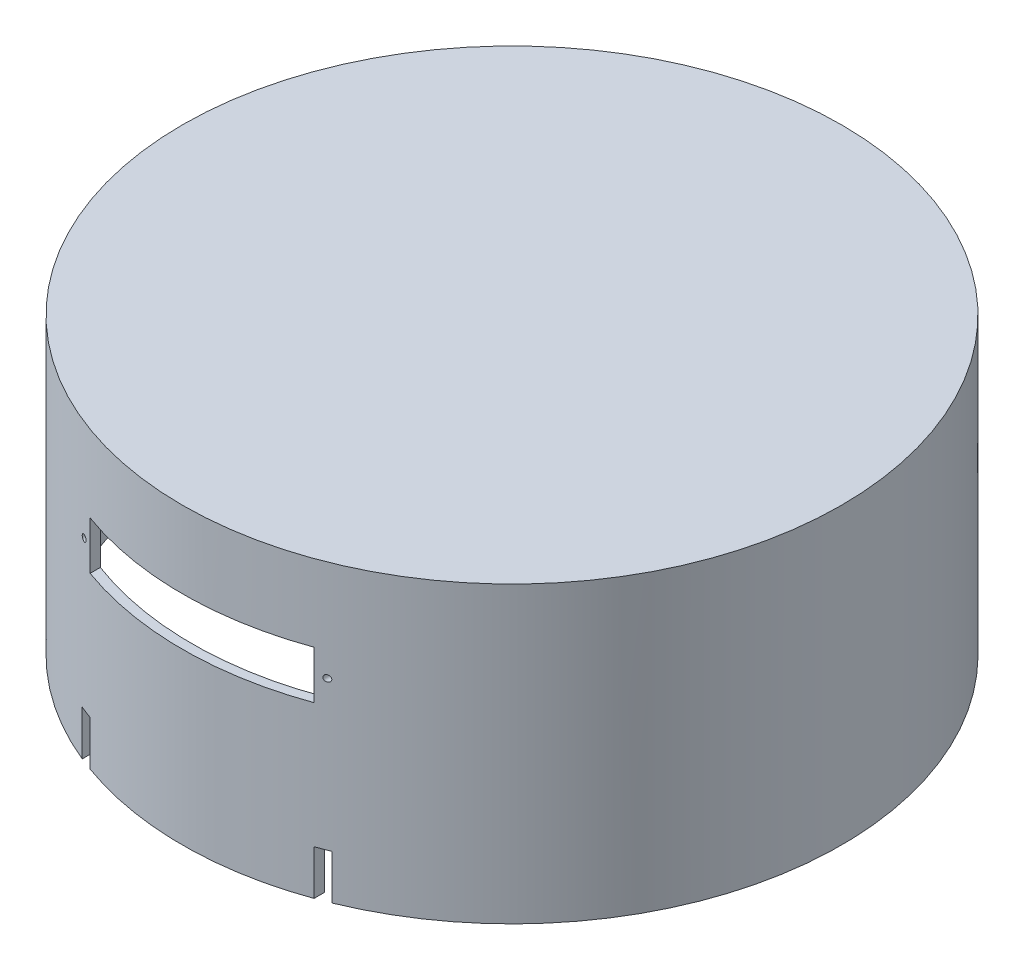
SolidWorks part; units mm, degrees
ref_plane "前视基准面" through (0, 0, 0) normal (0, 0, 1) x (1, 0, 0)
ref_plane "上视基准面" through (0, 0, 0) normal (0, 1, 0) x (1, 0, 0)
ref_plane "右视基准面" through (0, 0, 0) normal (1, 0, 0) x (0, 0, -1)
other "Configuration Table"
sketch "草图1" plane through (0, 0, 0) normal (0, 1, 0) x (1, 0, 0)
  circle A0 centre (0, 0) radius 103
  circle A1 centre (0, 0) radius 100
  dimension "D1" = 206
  dimension "D2" = 200
extrude "凸台-拉伸1" add sketch "草图1" along normal blind 63
sketch "草图2" plane through (0, 63, 0) normal (0, 1, 0) x (1, 0, 0)
  circle A0 centre (0, 0) radius 103
extrude "凸台-拉伸2" add sketch "草图2" along normal blind 2
sketch "草图4" plane through (0, 63, 0) normal (0, -1, 0) x (1, 0, 0)
  line L0 (0, 0) -> (177.2254, 0) construction
  line L1 (0, 0) -> (-156.419, 0) construction
  line L2 (-67, 0) -> (-67, -60)
  line L3 (-67, -60) -> (-65, -60)
  line L4 (-65, -60) -> (-65, 0)
  line L5 (-65, 0) -> (-67, 0)
  line L6 (67, 0) -> (67, -60)
  line L7 (67, -60) -> (65, -60)
  line L8 (65, -60) -> (65, 0)
  line L9 (65, 0) -> (67, 0)
  line L10 (-60, 0) -> (-60, 2)
  line L11 (-60, 2) -> (60, 2)
  line L12 (60, 2) -> (60, 0)
  line L13 (60, 0) -> (-60, 0)
  dimension "D1" = 65
  dimension "D2" = 2
  dimension "D3" = 2
  dimension "D4" = 65
  dimension "D5" = 60
  dimension "D6" = 60
  dimension "D7" = 2
  dimension "D8" = 5
  dimension "D9" = 5
extrude "凸台-拉伸3" add sketch "草图4" along normal blind 10
sketch "草图5" plane through (0, 0, 2) normal (0, 0, 1) x (1, 0, 0)
  line L0 (103, 0) -> (103, 65) construction
  line L1 (-35, 41) -> (35, 41)
  line L2 (-35, 41) -> (-35, 26)
  line L3 (-35, 26) -> (35, 26)
  line L4 (35, 41) -> (35, 26)
  line L5 (-103, 65) -> (-103, 0) construction
  line L6 (103, 65) -> (-103, 65) construction
  circle A0 centre (-38, 33.5) radius 1
  circle A1 centre (38, 33.5) radius 1
  dimension "D7" = 2
  dimension "D9" = 2
  dimension "D1" = 15
  dimension "D2" = 70
  dimension "D3" = 68
  dimension "D4" = 68
  dimension "D5" = 24
  dimension "D6" = 3
  dimension "D8" = 3
  dimension "D10" = 7.5
  dimension "D11" = 7.5
extrude "切除-拉伸1" cut sketch "草图5" along normal blind 1000
sketch "草图6" plane through (0, 63, 0) normal (0, -1, 0) x (1, 0, 0)
  line L0 (60, 2) -> (-60, 2) construction
  line L1 (-85, 5) -> (55, 5) construction
  line L2 (-85, 5) -> (-85, 33)
  line L3 (-85, 33) -> (55, 33) construction
  line L5 (-60, 2) -> (-60, 0) construction
  line L6 (53.5, 31.5) -> (53.5, 33)
  line L7 (-83.5, 31.5) -> (53.5, 31.5)
  line L8 (-83.5, 31.5) -> (-83.5, 6.5)
  line L9 (-83.5, 6.5) -> (53.5, 6.5)
  line L11 (53.5, 6.5) -> (53.5, 5)
  line L12 (-85, 5) -> (53.5, 5)
  line L13 (-85, 33) -> (53.5, 33)
  point P8 (-60, 1)
  dimension "D1" = 28
  dimension "D2" = 140
  dimension "D3" = 3
  dimension "D4" = 25
  dimension "D5" = 1.5
  dimension "D6" = 1.5
  dimension "D7" = 1.5
  dimension "D8" = 28
  dimension "D9" = 137
  dimension "D10" = 138.5
extrude "凸台-拉伸4" add sketch "草图6" along normal blind 20
sketch "草图7" plane through (0, 0, 0) normal (0, 0, -1) x (-1, 0, 0)
  line L0 (-100, 63) -> (100, 63) construction
  line L1 (-72, 63) -> (-67, 63)
  line L2 (-72, 63) -> (-72, 23)
  line L3 (-72, 23) -> (72, 23)
  line L4 (72, 63) -> (72, 23)
  line L5 (67, 53) -> (67, 63) construction
  line L6 (-67, 53) -> (-67, 63) construction
  line L7 (-65, 63) -> (65, 63)
  line L9 (-67, 63) -> (-67, 53)
  line L10 (-67, 53) -> (-65, 53)
  line L11 (-65, 63) -> (-65, 53)
  line L13 (65, 63) -> (65, 53)
  line L14 (65, 53) -> (67, 53)
  line L15 (67, 63) -> (67, 53)
  line L16 (67, 63) -> (72, 63)
  dimension "D1" = 5
  dimension "D2" = 5
  dimension "D3" = 40
  dimension "D4" = 144
extrude "切除-拉伸2" cut sketch "草图7" along normal blind 150 contours L3 L4 L16 L15 L14 L13 L7 L11 L10 L9 L1 L2
sketch "草图10" plane through (0, 53, 0) normal (0, -1, 0) x (1, 0, 0)
  line L1 (-60, 2) -> (60, 2)
  line L2 (-60, 2) -> (-60, 0)
  line L3 (-60, 0) -> (60, 0)
  line L4 (60, 2) -> (60, 0)
  line L5 (-67, 0) -> (-65, 0)
  line L6 (-67, 0) -> (-67, -60)
  line L7 (-67, -60) -> (-65, -60)
  line L8 (-65, 0) -> (-65, -60)
  line L9 (65, 0) -> (67, 0)
  line L10 (65, 0) -> (65, -60)
  line L11 (65, -60) -> (67, -60)
  line L12 (67, 0) -> (67, -60)
extrude "切除-拉伸3" cut sketch "草图10" against normal blind 5
sketch "草图11" plane through (0, 53, 0) normal (0, -1, 0) x (1, 0, 0)
  line L1 (-67.6882, -73.6091) -> (-64.5381, -73.6091)
  line L2 (-67.6882, -73.6091) -> (-67.6882, -80.2735)
  line L3 (-67.6882, -80.2735) -> (-64.5381, -80.2735)
  line L4 (-64.5381, -73.6091) -> (-64.5381, -80.2735)
  line L5 (63.9807, -74.0444) -> (67.4393, -74.0444)
  line L6 (63.9807, -74.0444) -> (63.9807, -80.2735)
  line L7 (63.9807, -80.2735) -> (67.4393, -80.2735)
  line L8 (67.4393, -74.0444) -> (67.4393, -80.2735)
  circle A0 centre (0, 0) radius 100 construction
  circle A1 centre (0, 0) radius 103 construction
extrude "切除-拉伸4" cut sketch "草图11" against normal blind 5
sketch "草图13" plane through (0, 0, 0) normal (0, -1, 0) x (1, 0, 0)
  circle A0 centre (0, 0) radius 103
  circle A1 centre (0, 0) radius 100
extrude "凸台-拉伸5" add sketch "草图13" along normal blind 17
sketch "草图15" plane through (0, -17, 0) normal (0, -1, 0) x (1, 0, 0)
  line L0 (-39, 95.331) -> (-39, 92.0815)
  line L1 (-39, 95.331) -> (-39, 92.0815) construction
  line L2 (-39, 92.0815) -> (-35, 92.0815)
  line L3 (-35, 92.0815) -> (-35, 100)
  line L4 (-35, 100) -> (-39, 100)
  line L5 (-39, 100) -> (-39, 95.331)
  line L6 (35, 96.871) -> (35, 92.0815)
  line L7 (35, 92.0815) -> (39, 92.0815)
  line L8 (39, 92.0815) -> (39, 96.871)
  line L9 (39, 96.871) -> (35, 96.871)
  circle A0 centre (0, 0) radius 100 construction
  dimension "D1" = 4
  dimension "D2" = 4
  dimension "D3" = 7.9185
extrude "切除-拉伸5" cut sketch "草图15" against normal blind 4
sketch "草图16" plane through (0, -17, 0) normal (0, -1, 0) x (1, 0, 0)
  line L0 (39, 92.0815) -> (39, -113.0415) construction
  line L1 (35, 93.675) -> (35, -113.0415) construction
  line L2 (-35, 93.675) -> (-35, -109.5119) construction
  line L3 (-39, 92.0815) -> (-39, -113.0415) construction
  line L4 (35, -96.871) -> (39, -96.871)
  line L5 (39, -96.871) -> (39, -92.0815)
  line L6 (39, -92.0815) -> (35, -92.0815)
  line L7 (35, -92.0815) -> (35, -96.871)
  line L8 (-35, -96.871) -> (-39, -96.871)
  line L9 (-39, -96.871) -> (-39, -92.0815)
  line L10 (-39, -92.0815) -> (-35, -92.0815)
  line L11 (-35, -92.0815) -> (-35, -96.871)
  arc A0 (-39, 95.331) -> (39, 95.331) centre (0, 0) ccw construction
  arc A1 (-39, 92.0815) -> (39, 92.0815) centre (0, 0) ccw construction
extrude "切除-拉伸6" cut sketch "草图16" against normal blind 4 and the other way blind 15
sketch "草图18" plane through (0, -17, 0) normal (0, -1, 0) x (1, 0, 0)
  circle A0 centre (0, 0) radius 100
  circle A1 centre (0, 0) radius 103
  dimension "D1" = 200
  dimension "D2" = 206
extrude "凸台-拉伸6" add sketch "草图18" along normal blind 10
sketch "草图19" plane through (0, -27, 0) normal (0, -1, 0) x (1, 0, 0)
  line L1 (-39, -92.0815) -> (-35, -92.0815)
  line L2 (-39, -92.0815) -> (-39, -96.871)
  line L3 (-39, -96.871) -> (-35, -96.871)
  line L4 (-35, -92.0815) -> (-35, -96.871)
  line L5 (39, -92.0815) -> (35, -92.0815)
  line L6 (39, -92.0815) -> (39, -96.871)
  line L7 (39, -96.871) -> (35, -96.871)
  line L8 (35, -92.0815) -> (35, -96.871)
  line L9 (-39, 92.0815) -> (-35, 92.0815)
  line L10 (-39, 92.0815) -> (-39, 96.871)
  line L11 (-39, 96.871) -> (-35, 96.871)
  line L12 (-35, 92.0815) -> (-35, 96.871)
  line L13 (35, 96.871) -> (39, 96.871)
  line L14 (35, 96.871) -> (35, 92.0815)
  line L15 (35, 92.0815) -> (39, 92.0815)
  line L16 (39, 96.871) -> (39, 92.0815)
extrude "切除-拉伸7" cut sketch "草图19" against normal blind 10
